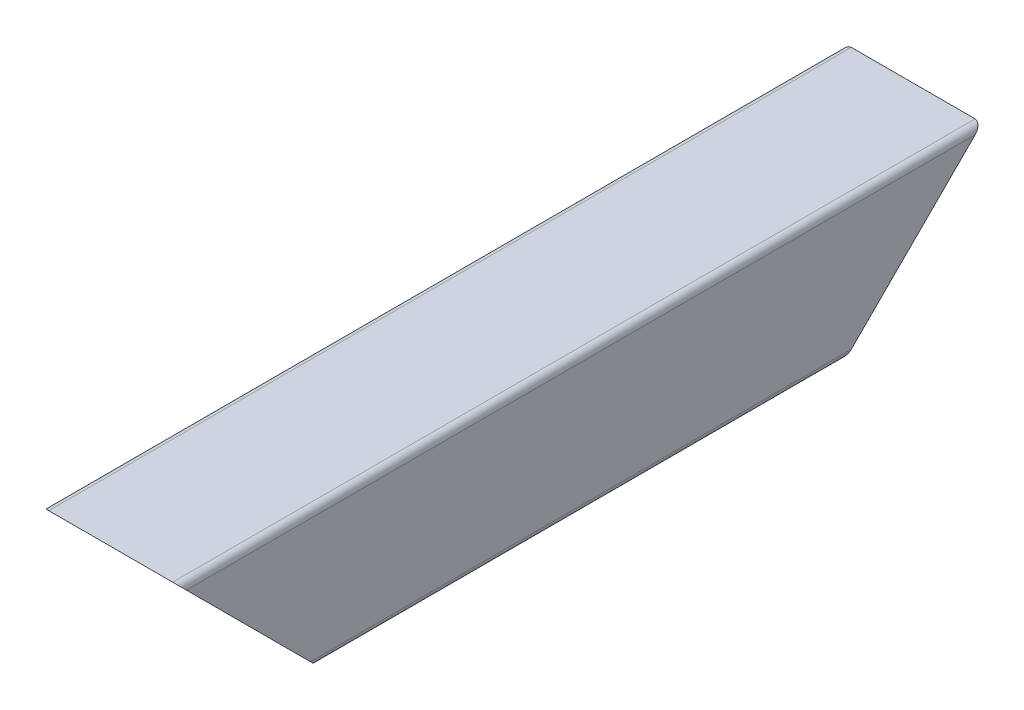
SolidWorks part; units mm, degrees
ref_plane "Płaszczyzna przednia" through (0, 0, 0) normal (0, 0, 1) x (1, 0, 0)
ref_plane "Płaszczyzna górna" through (0, 0, 0) normal (0, 1, 0) x (1, 0, 0)
ref_plane "Płaszczyzna prawa" through (0, 0, 0) normal (1, 0, 0) x (0, 0, -1)
sketch "Szkic1" plane through (0, 0, 0) normal (0, 0, 1) x (1, 0, 0)
  line L0 (3, 6) -> (3, 54)
  line L1 (3, 0) -> (57, 0)
  line L2 (0, 3) -> (0, 57)
  line L3 (3, 60) -> (57, 60)
  line L4 (60, 3) -> (60, 57)
  line L5 (0, 0) -> (42.6554, 0)
  line L6 (0, 0) -> (0, 31.4913)
  line L7 (6, 57) -> (54, 57)
  line L8 (57, 6) -> (57, 54)
  line L9 (6, 3) -> (54, 3)
  arc A0 (57, 60) -> (60, 57) centre (57, 57) cw
  arc A1 (54, 57) -> (57, 54) centre (54, 54) cw
  arc A2 (57, 0) -> (60, 3) centre (57, 3) ccw
  arc A3 (57, 6) -> (54, 3) centre (54, 6) cw
  arc A4 (3, 6) -> (6, 3) centre (6, 6) ccw
  arc A5 (3, 0) -> (0, 3) centre (3, 3) cw
  arc A6 (3, 54) -> (6, 57) centre (6, 54) cw
  arc A7 (0, 57) -> (3, 60) centre (3, 57) cw
  dimension "D1" = 3
extrude "Dodanie-wyciągnięcie1" add sketch "Szkic1" along normal blind 350 contours A7 L2 A5 L1 A2 L4 A0 L3 L0 A6 L7 A1 L8 A3 L9 A4
ref_plane "Płaszczyzna1" through (0, -145, 145) normal (0, -0.7071, 0.7071) x (1, 0, 0)
sketch "Szkic2" plane through (0, -145, 145) normal (0, -0.7071, 0.7071) x (1, 0, 0)
  line L1 (-30.4012, 317.9451) -> (109.7027, 317.9451)
  line L2 (-30.4012, 317.9451) -> (-30.4012, 188.9863)
  line L3 (-30.4012, 188.9863) -> (109.7027, 188.9863)
  line L4 (109.7027, 317.9451) -> (109.7027, 188.9863)
extrude "Wytnij-wyciągnięcie1" cut sketch "Szkic2" along normal through all contours L1 L4 L3 L2
ref_plane "Płaszczyzna2" through (0, 30, 30) normal (0, -0.7071, -0.7071) x (1, 0, 0)
sketch "Szkic3" plane through (0, 30, 30) normal (0, -0.7071, -0.7071) x (1, 0, 0)
  line L1 (117.2349, -75.108) -> (-63.0461, -75.108)
  line L2 (117.2349, -75.108) -> (117.2349, 63.861)
  line L3 (117.2349, 63.861) -> (-63.0461, 63.861)
  line L4 (-63.0461, -75.108) -> (-63.0461, 63.861)
extrude "Wytnij-wyciągnięcie2" cut sketch "Szkic3" along normal through all contours L4 L3 L2 L1
